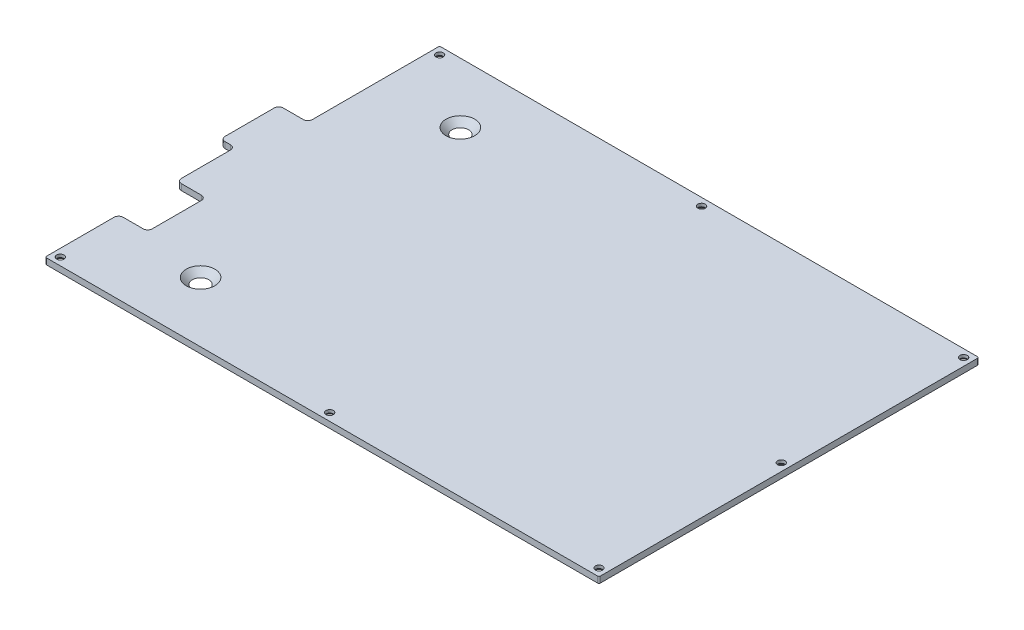
SolidWorks part; units mm, degrees
material "6061-T6 (SS)"
ref_plane "Front Plane" through (0, 0, 0) normal (0, 0, 1) x (1, 0, 0)
ref_plane "Top Plane" through (0, 0, 0) normal (0, 1, 0) x (1, 0, 0)
ref_plane "Right Plane" through (0, 0, 0) normal (1, 0, 0) x (0, 0, -1)
sketch "Sketch1" plane through (0, 0, 0) normal (0, 1, 0) x (1, 0, 0)
  line L0 (0, 0) -> (0, 124.3)
  line L1 (0, 124.3) -> (-176.45, 124.3)
  line L2 (-176.45, 124.3) -> (-176.45, 81.2)
  line L3 (-176.45, 81.2) -> (-185.975, 81.2)
  line L4 (-185.975, 81.2) -> (-185.975, 62.15)
  line L5 (-185.975, 62.15) -> (-181.2125, 62.15)
  line L6 (-181.2125, 62.15) -> (-181.2125, 43.1)
  line L7 (-181.2125, 43.1) -> (-171.6875, 43.1)
  line L8 (-171.6875, 43.1) -> (-171.6875, 24.05)
  line L9 (-171.6875, 24.05) -> (-181.2125, 24.05)
  line L10 (-181.2125, 24.05) -> (-181.2125, 0)
  line L11 (-181.2125, 0) -> (0, 0)
  dimension "D2" = 19.05
  dimension "D3" = 4.7625
  dimension "D4" = 9.525
  dimension "D6" = 176.45
  dimension "D7" = 9.525
  dimension "D5" = 43.1
  dimension "D1" = 24.05
extrude "Plate Frame" add sketch "Sketch1" along normal blind 2
sketch "Sketch2" plane through (0, 0, 0) normal (0, -1, 0) x (1, 0, 0)
  line L0 (-178.7125, -2.5) -> (-90.6063, -2.5) construction
  line L1 (-90.6063, -2.5) -> (-2.5, -2.5) construction
  line L2 (-2.5, -2.5) -> (-2.5, -62.15) construction
  line L3 (-2.5, -62.15) -> (-2.5, -121.8) construction
  line L4 (-2.5, -121.8) -> (-88.225, -121.8) construction
  line L5 (-88.225, -121.8) -> (-173.95, -121.8) construction
  line L6 (-181.2125, 0) -> (0, 0) construction
  line L7 (-181.2125, -24.05) -> (-181.2125, 0) construction
  line L8 (0, 0) -> (0, -124.3) construction
  line L9 (0, -124.3) -> (-176.45, -124.3) construction
  line L10 (-176.45, -124.3) -> (-176.45, -81.2) construction
  point P0 (-178.7125, -2.5)
  point P1 (-90.6063, -2.5)
  point P2 (-2.5, -2.5)
  point P3 (-2.5, -62.15)
  point P4 (-2.5, -121.8)
  point P5 (-88.225, -121.8)
  point P6 (-173.95, -121.8)
  dimension "D1" = 2.5
  dimension "D2" = 2.5
  dimension "D3" = 2.5
  dimension "D4" = 2.5
  dimension "D5" = 2.5
hole_wizard "CSK for M2 Flat Head Machine Screw1" positions "Sketch3" profile "Sketch4" countersink size "M2" standard "ANSI Metric" end condition through all
sketch "Sketch3" plane through (0, 0, 0) normal (0, -1, 0) x (-1, 0, 0)
  point P0 (178.7125, 2.5)
  point P3 (90.6063, 2.5)
  point P6 (2.5, 2.5)
  point P9 (2.5, 62.15)
  point P12 (2.5, 121.8)
  point P15 (88.225, 121.8)
  point P18 (173.95, 121.8)
sketch "Sketch4" plane through (-178.7125, 0, -2.5) normal (1, 0, 0) x (0, 0, -1)
  line L0 (0, 0) -> (0, 2)
  line L1 (0, 2) -> (1.2, 2)
  line L2 (1.2, 2) -> (1.2, 1)
  line L3 (1.2, 1) -> (2.2, 0)
  line L5 (2.2, 0) -> (0, 0)
  line L6 (-1.2, 1) -> (-2.2, 0) construction
  line L11 (0, -6.35) -> (0, 107.95) construction
  dimension "Thru Hole Dia." = 2.4
  dimension "Thru Hole Depth" = 2
  dimension "Near C'Sink Dia." = 4.4
  dimension "Near C'Sink Angle" = 90
sketch "Sketch5" plane through (0, 2, 0) normal (0, 1, 0) x (1, 0, 0)
  line L0 (-150, 104.65) -> (-150, 19.65) construction
  line L1 (-150, 62.15) -> (-2.5, 62.15) construction
  line L3 (0, 0) -> (0, 124.3) construction
  line L4 (-150, 104.65) -> (-25, 104.65) construction
  line L5 (-25, 104.65) -> (-25, 62.15) construction
  dimension "D1" = 85
  dimension "D2" = 150
  dimension "D3" = 25
hole_wizard "CSK for M4 Flat Head Machine Screw1" positions "Sketch6" profile "Sketch7" countersink size "M4" standard "ANSI Metric" end condition through all
sketch "Sketch6" plane through (0, 2, 0) normal (0, 1, 0) x (1, 0, 0)
  point P0 (-150, 104.65)
  point P3 (-150, 19.65)
  point P12 (0, 0)
sketch "Sketch7" plane through (-150, 2, -104.65) normal (1, 0, 0) x (0, 0, 1)
  line L0 (0, 0) -> (0, 2)
  line L1 (0, 2) -> (2.25, 2)
  line L2 (2.25, 2) -> (2.25, 2.45)
  line L3 (2.25, 2.45) -> (4.7, 0)
  line L5 (4.7, 0) -> (0, 0)
  line L6 (-2.25, 2.45) -> (-4.7, 0) construction
  line L11 (0, -6.35) -> (0, 107.95) construction
  dimension "Thru Hole Dia." = 4.5
  dimension "Thru Hole Depth" = 2
  dimension "Near C'Sink Dia." = 9.4
  dimension "Near C'Sink Angle" = 90
fillet "Fillet1" radius 1.5 8 edges at (-171.6875, 1, -24.05) (-181.2125, 1, -24.05) (-171.6875, 1, -43.1) (-181.2125, 1, -62.15) (-181.2125, 1, -43.1) (-185.975, 1, -62.15) (-185.975, 1, -81.2) (-176.45, 1, -81.2)
fillet "Fillet2" radius 0.5 4 edges at (-176.45, 1, -124.3) (-181.2125, 1, 0) (0, 1, -124.3) (0, 1, 0)
equation "\"D3@Sketch1\"=19.05/4"
equation "\"D4@Sketch1\"=19.05/2"
equation "\"D5@Sketch1\"=2*19.05 + 5"
equation "\"D1@Sketch1\"=19.05 + 5"
equation "\"D6@Sketch1\"=19.05*9 + 5"
